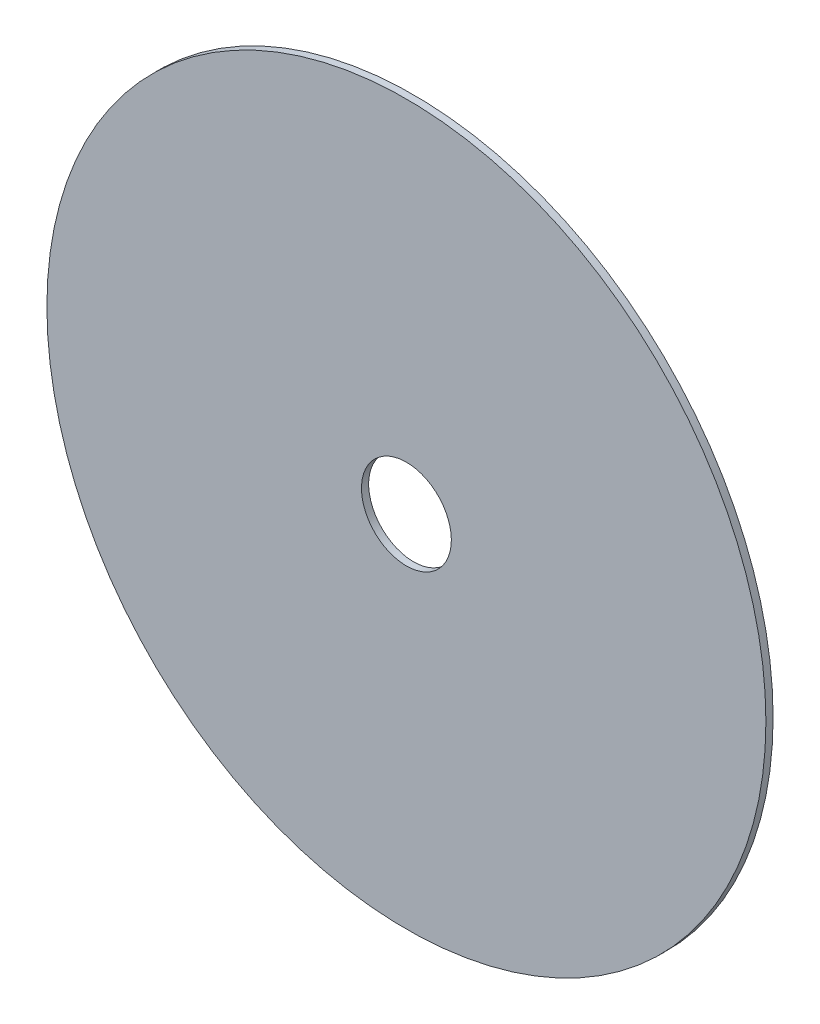
SolidWorks part; units mm, degrees
ref_plane "Plan de face" through (0, 0, 0) normal (0, 0, 1) x (1, 0, 0)
ref_plane "Plan de dessus" through (0, 0, 0) normal (0, 1, 0) x (1, 0, 0)
ref_plane "Plan de droite" through (0, 0, 0) normal (1, 0, 0) x (0, 0, -1)
sketch "Esquisse1" plane through (0, 0, 0) normal (0, 0, 1) x (1, 0, 0)
  circle A0 centre (0, 0) radius 60
  circle A1 centre (0, 0) radius 7.5
  dimension "D1" = 15
  dimension "D2" = 120
extrude "Boss.-Extru.1" add sketch "Esquisse1" along normal blind 1.2
